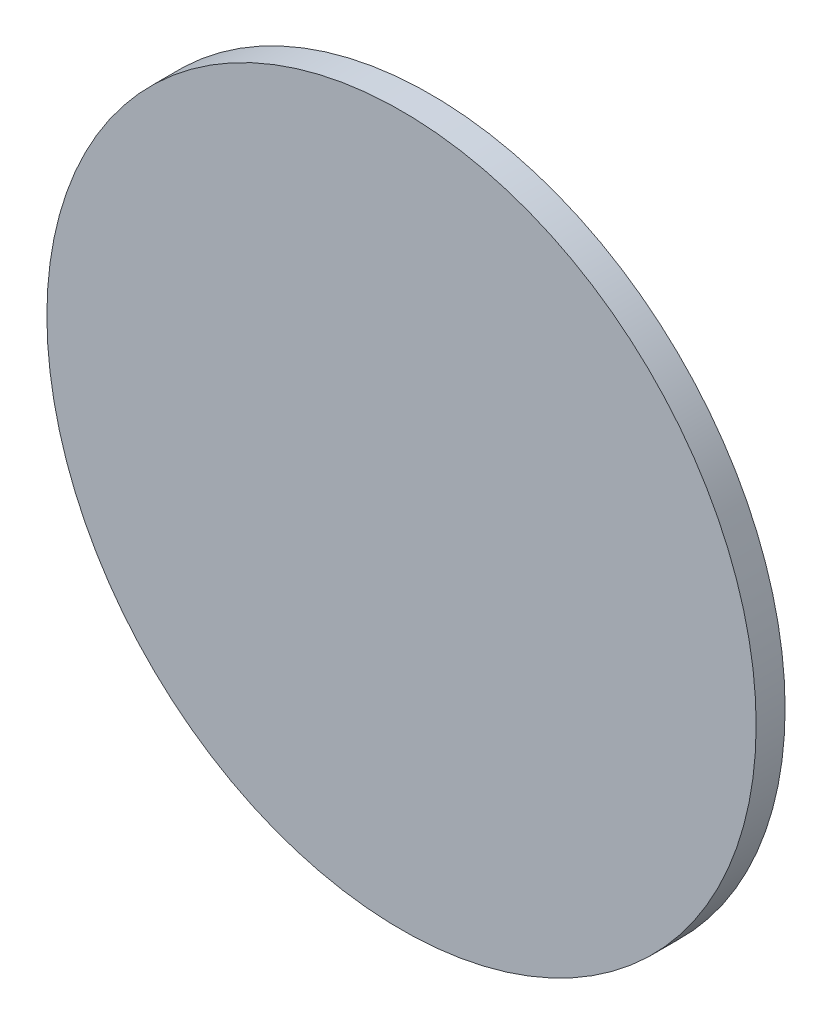
SolidWorks part; units mm, degrees
ref_plane "Front Plane" through (0, 0, 0) normal (0, 0, 1) x (1, 0, 0)
ref_plane "Top Plane" through (0, 0, 0) normal (0, 1, 0) x (1, 0, 0)
ref_plane "Right Plane" through (0, 0, 0) normal (1, 0, 0) x (0, 0, -1)
sketch "Sketch1" plane through (0, 0, 0) normal (0, 0, 1) x (1, 0, 0)
  circle A0 centre (0, 0) radius 122.5
  dimension "D1" = 245
extrude "Boss-Extrude1" add sketch "Sketch1" along normal blind 10
